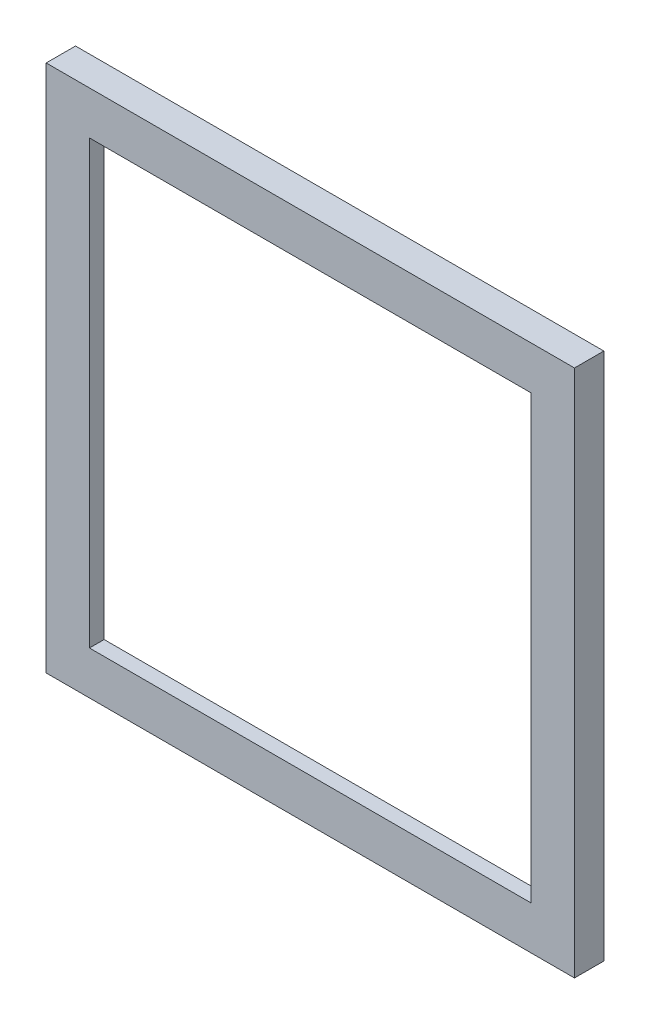
SolidWorks part; units mm, degrees
ref_plane "Plan de face" through (0, 0, 0) normal (0, 0, 1) x (1, 0, 0)
ref_plane "Plan de dessus" through (0, 0, 0) normal (0, 1, 0) x (1, 0, 0)
ref_plane "Plan de droite" through (0, 0, 0) normal (1, 0, 0) x (0, 0, -1)
sketch "Esquisse1" plane through (0, 0, 0) normal (0, 0, 1) x (1, 0, 0)
  line L1 (-18, -18) -> (18, -18)
  line L2 (-18, -18) -> (-18, 18)
  line L3 (-18, 18) -> (18, 18)
  line L4 (18, -18) -> (18, 18)
  line L5 (-18, -18) -> (18, 18) construction
  line L6 (-18, 18) -> (18, -18) construction
  line L7 (-15.05, -15.05) -> (15.05, -15.05)
  line L8 (-15.05, -15.05) -> (-15.05, 15.05)
  line L9 (-15.05, 15.05) -> (15.05, 15.05)
  line L10 (15.05, -15.05) -> (15.05, 15.05)
  line L11 (-15.05, -15.05) -> (15.05, 15.05) construction
  line L12 (-15.05, 15.05) -> (15.05, -15.05) construction
  point P0 (0, 0)
  point P6 (0, 0)
  dimension "D1" = 36
  dimension "D2" = 36
  dimension "D3" = 30.1
extrude "Boss.-Extru.1" add sketch "Esquisse1" along normal blind 2
sketch "Esquisse2" plane through (0, 0, 0) normal (0, 0, -1) x (-1, 0, 0)
  line L1 (-17, -17) -> (17, -17)
  line L2 (-17, -17) -> (-17, 17)
  line L3 (-17, 17) -> (17, 17)
  line L4 (17, -17) -> (17, 17)
  line L5 (-17, -17) -> (17, 17) construction
  line L6 (-17, 17) -> (17, -17) construction
  point P0 (0, 0)
  dimension "D1" = 34
  dimension "D2" = 34
extrude "Enlèv. mat.-Extru.1" cut sketch "Esquisse2" against normal blind 1
